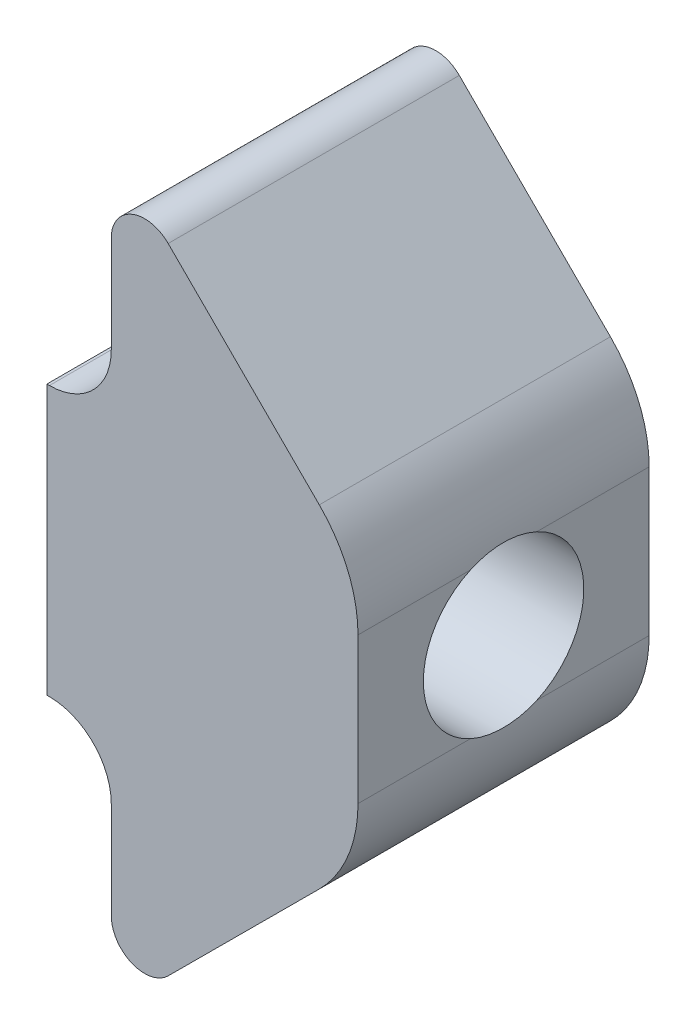
SolidWorks part; units mm, degrees
ref_plane "Front Plane" through (0, 0, 0) normal (0, 0, 1) x (1, 0, 0)
ref_plane "Top Plane" through (0, 0, 0) normal (0, 1, 0) x (1, 0, 0)
ref_plane "Right Plane" through (0, 0, 0) normal (1, 0, 0) x (0, 0, -1)
sketch "Sketch1" plane through (0, 0, 0) normal (0, 0, 1) x (1, 0, 0)
  line L0 (-11.5951, -2.9385) -> (-11.5951, 2.9385)
  line L1 (-11.5951, 2.9385) -> (-11.5392, 2.9385)
  line L2 (-10.1902, 4.2875) -> (-10.1902, 6.4021)
  line L3 (-8.949, 6.917) -> (-5.6529, 3.6284)
  line L4 (-4.8085, 1.5932) -> (-4.8085, -1.5932)
  line L5 (-5.6529, -3.6284) -> (-8.949, -6.917)
  line L6 (-10.1902, -6.4021) -> (-10.1902, -4.2875)
  line L7 (-11.5392, -2.9385) -> (-11.5951, -2.9385)
  line L8 (-11.651, 2.9385) -> (-11.5392, 2.9385) construction
  line L9 (-11.5392, -2.9385) -> (-11.651, -2.9385) construction
  line L10 (-11.5951, -2.9385) -> (-11.9739, -2.9385)
  line L119 (-11.651, 3.2385) -> (-11.5392, 3.2385) construction
  line L120 (-10.4902, 4.2875) -> (-10.4902, 6.4021) construction
  line L121 (-8.7371, 7.1294) -> (-5.441, 3.8408) construction
  line L122 (-4.5085, 1.5932) -> (-4.5085, -1.5932) construction
  line L123 (-5.441, -3.8408) -> (-8.7371, -7.1294) construction
  line L124 (-10.4902, -6.4021) -> (-10.4902, -4.2875) construction
  line L125 (-11.5392, -3.2385) -> (-11.651, -3.2385) construction
  arc A0 (-11.5392, 2.9385) -> (-10.1902, 4.2875) centre (-11.5392, 4.2875) ccw
  arc A1 (-8.949, 6.917) -> (-10.1902, 6.4021) centre (-9.4628, 6.4021) ccw
  arc A2 (-4.8085, 1.5932) -> (-5.6529, 3.6284) centre (-7.6835, 1.5932) ccw
  arc A3 (-5.6529, -3.6284) -> (-4.8085, -1.5932) centre (-7.6835, -1.5932) ccw
  arc A4 (-10.1902, -6.4021) -> (-8.949, -6.917) centre (-9.4628, -6.4021) ccw
  arc A5 (-10.1902, -4.2875) -> (-11.5392, -2.9385) centre (-11.5392, -4.2875) ccw
  arc A142 (-11.5392, 3.2385) -> (-10.4902, 4.2875) centre (-11.5392, 4.2875) ccw construction
  arc A143 (-8.7371, 7.1294) -> (-10.4902, 6.4021) centre (-9.4628, 6.4021) ccw construction
  arc A144 (-4.5085, 1.5932) -> (-5.441, 3.8408) centre (-7.6835, 1.5932) ccw construction
  arc A145 (-5.441, -3.8408) -> (-4.5085, -1.5932) centre (-7.6835, -1.5932) ccw construction
  arc A146 (-10.4902, -6.4021) -> (-8.7371, -7.1294) centre (-9.4628, -6.4021) ccw construction
  arc A147 (-10.4902, -4.2875) -> (-11.5392, -3.2385) centre (-11.5392, -4.2875) ccw construction
  dimension "D1" = 0.3
  dimension "D2" = 5.8769
  dimension "D3" = 0.3788
extrude "Boss-Extrude1" add sketch "Sketch1" along normal blind 6.35 contours L0 L1 A0 L2 A1 L3 A2 L4 A3 L5 A4 L6 A5 L7
sketch "Sketch2" plane through (-11.5951, 0, 0) normal (-1, 0, 0) x (0, 0, 1)
  line L0 (3.175, 2.9385) -> (3.175, -2.9385) construction
  line L1 (6.35, 2.9385) -> (0, 2.9385) construction
  line L2 (6.35, -2.9385) -> (0, -2.9385) construction
  line L3 (0, 0) -> (6.35, 0) construction
  line L4 (0, -2.9385) -> (0, 2.9385) construction
  line L5 (6.35, -2.9385) -> (6.35, 2.9385) construction
  circle A0 centre (3.175, 0) radius 1.75
  dimension "D1" = 3.5
extrude "Cut-Extrude1" cut sketch "Sketch2" against normal up to next contours A0
fillet "Fillet1" radius 0.2 1 edges at (-11.5951, 0, 4.925)
